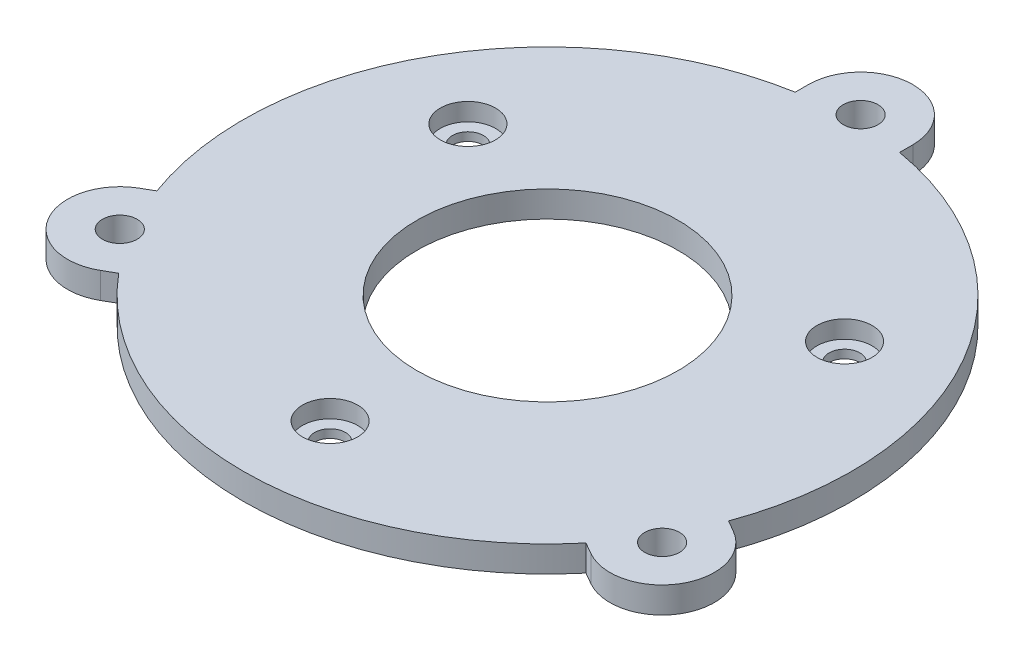
SolidWorks part; units mm, degrees
ref_plane "Front" through (0, 0, 0) normal (0, 0, 1) x (1, 0, 0)
ref_plane "Top" through (0, 0, 0) normal (0, 1, 0) x (1, 0, 0)
ref_plane "Right" through (0, 0, 0) normal (1, 0, 0) x (0, 0, -1)
sketch "Sketch1" plane through (0, 0, 0) normal (0, 1, 0) x (1, 0, 0)
  line L0 (0, 0) -> (0, 18) construction
  line L1 (-3, 0) -> (-3, 18)
  line L2 (3, 0) -> (3, 18)
  line L3 (-1.5, -2.5981) -> (14.0885, -11.5981)
  line L4 (1.5, 2.5981) -> (17.0885, -6.4019)
  line L5 (0, 0) -> (15.5885, -9) construction
  line L6 (-1.5, 2.5981) -> (-17.0885, -6.4019)
  line L7 (1.5, -2.5981) -> (-14.0885, -11.5981)
  line L8 (0, 0) -> (-15.5885, -9) construction
  circle A0 centre (0, 0) radius 17.5
  circle A1 centre (0, 0) radius 7.5
  arc A2 (-3, 0) -> (3, 0) centre (0, 0) ccw
  arc A3 (3, 18) -> (-3, 18) centre (0, 18) ccw
  circle A4 centre (0, 18) radius 1
  arc A5 (1.5, 2.5981) -> (-1.5, -2.5981) centre (0, 0) ccw
  arc A6 (14.0885, -11.5981) -> (17.0885, -6.4019) centre (15.5885, -9) ccw
  circle A7 centre (15.5885, -9) radius 1
  arc A8 (1.5, -2.5981) -> (-1.5, 2.5981) centre (0, 0) ccw
  arc A9 (-17.0885, -6.4019) -> (-14.0885, -11.5981) centre (-15.5885, -9) ccw
  circle A10 centre (-15.5885, -9) radius 1
  point P4 (0, 9)
  point P15 (7.7942, -4.5)
  point P23 (-7.7942, -4.5)
  dimension "D1" = 35
  dimension "D2" = 15
  dimension "D3" = 3
  dimension "D5" = 2
  dimension "D4" = 18
extrude "Boss-Extrude1" add sketch "Sketch1" along normal blind 1.5 contours A10 A0 L6 A9 L7 | A1 L1 A0 L6 | A10 A0 L7 A1 L6 | A1 L7 A0 L3 | A7 A0 L4 A1 L3 | A1 L4 A0 L2 | A4 A0 L2 A3 L1 | A4 A0 L1 A1 L2 | A7 A0 L3 A6 L4
sketch "Sketch2" plane through (0, 1.5, 0) normal (0, 1, 0) x (1, 0, 0)
  line L0 (0, 0) -> (0, -12.5) construction
  line L1 (0, 0) -> (-10.8253, 6.25) construction
  line L2 (0, 0) -> (10.8253, 6.25) construction
  dimension "D1" = 12.5
  dimension "D2" = 3
hole_wizard "CBORE for #0 Socket Head Cap Screw1" positions "Sketch3" profile "Sketch4" counterbore size "#0" standard "ANSI Inch" end condition through all
sketch "Sketch3" plane through (0, 1.5, 0) normal (0, 1, 0) x (1, 0, 0)
  point P0 (-10.8253, 6.25)
  point P3 (10.8253, 6.25)
  point P6 (0, -12.5)
sketch "Sketch4" plane through (-10.8253, 1.5, -6.25) normal (1, 0, 0) x (0, 0, 1)
  line L0 (0, 0) -> (0, 1.5)
  line L1 (0, 1.5) -> (0.889, 1.5)
  line L3 (0.889, 1.5) -> (0.889, 1.016)
  line L4 (0.889, 1.016) -> (1.5875, 1.016)
  line L5 (1.5875, 1.016) -> (1.5875, 0)
  line L7 (1.5875, 0) -> (0, 0)
  line L11 (0, -6.35) -> (0, 107.95) construction
  dimension "Thru Hole Dia." = 1.778
  dimension "Thru Hole Depth" = 1.5
  dimension "C'Bore Dia." = 3.175
  dimension "C'Bore Depth" = 1.016
